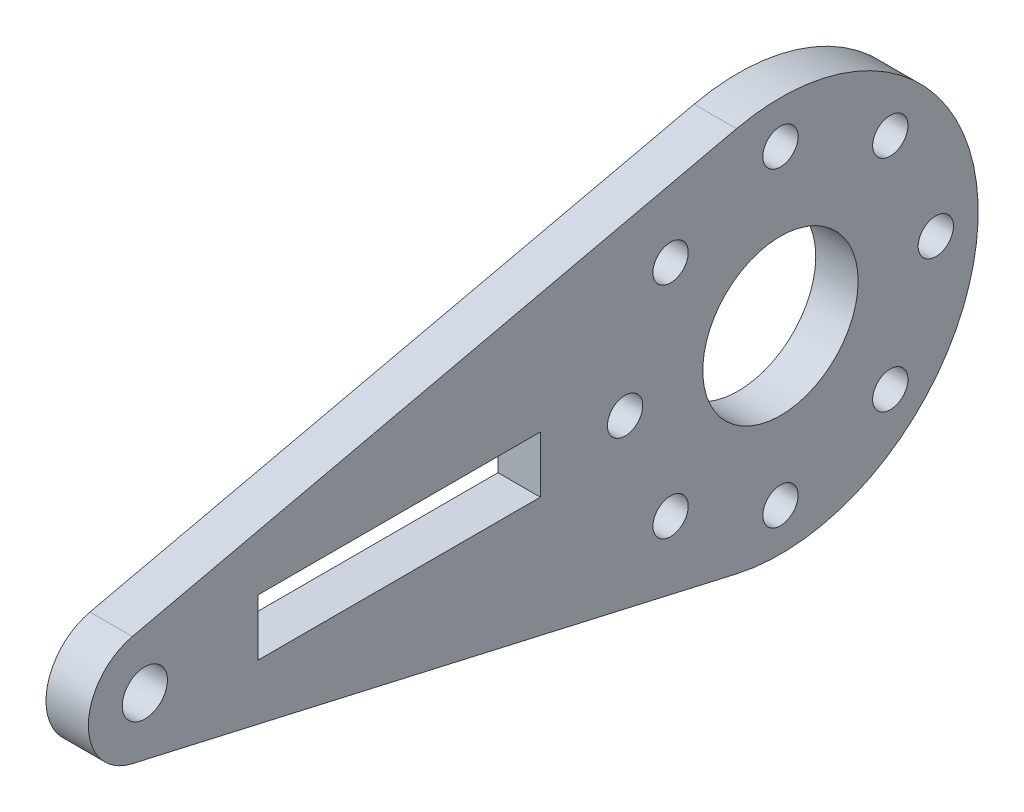
SolidWorks part; units mm, degrees
ref_plane "Front Plane" through (0, 0, 0) normal (0, 0, 1) x (1, 0, 0)
ref_plane "Top Plane" through (0, 0, 0) normal (0, 1, 0) x (1, 0, 0)
ref_plane "Right Plane" through (0, 0, 0) normal (1, 0, 0) x (0, 0, -1)
sketch "Sketch1" plane through (0, 0, 0) normal (1, 0, 0) x (0, 0, -1)
  line L0 (0, 0) -> (-45, 0) construction
  line L1 (-45.8889, 3.9) -> (-3.1111, 13.6499)
  line L2 (-45.8889, -3.9) -> (-3.1111, -13.6499)
  line L4 (-17, -2) -> (-37, -2)
  line L5 (-17, -2) -> (-17, 2)
  line L6 (-17, 2) -> (-37, 2)
  line L7 (-37, -2) -> (-37, 2)
  line L8 (-17, -2) -> (-37, 2) construction
  line L9 (-17, 2) -> (-37, -2) construction
  arc A0 (-3.1111, -13.6499) -> (-3.1111, 13.6499) centre (0, 0) ccw
  circle A1 centre (-45, 0) radius 1.6
  arc A2 (-45.8889, 3.9) -> (-45.8889, -3.9) centre (-45, 0) ccw
  circle A3 centre (0, 0) radius 5.5
  point P5 (-27, 0)
  dimension "D1" = 28
  dimension "D3" = 3.2
  dimension "D4" = 8
  dimension "D5" = 11
  dimension "D2" = 45
  dimension "D6" = 20
  dimension "D7" = 4
  dimension "D8" = 8
extrude "Boss-Extrude1" add sketch "Sketch1" along normal blind 3
sketch "Sketch2" plane through (3, 0, 0) normal (1, 0, 0) x (0, 0, -1)
  circle A0 centre (0, 0) radius 11 construction
  circle A1 centre (0, 11) radius 1.25
  dimension "D1" = 22
  dimension "D2" = 2.5
extrude "Cut-Extrude1" cut sketch "Sketch2" against normal up to next
pattern_circular "CirPattern1" count 8 over 360 about axis through (0, 0, 0) along (1, 0, 0) of "Cut-Extrude1"
